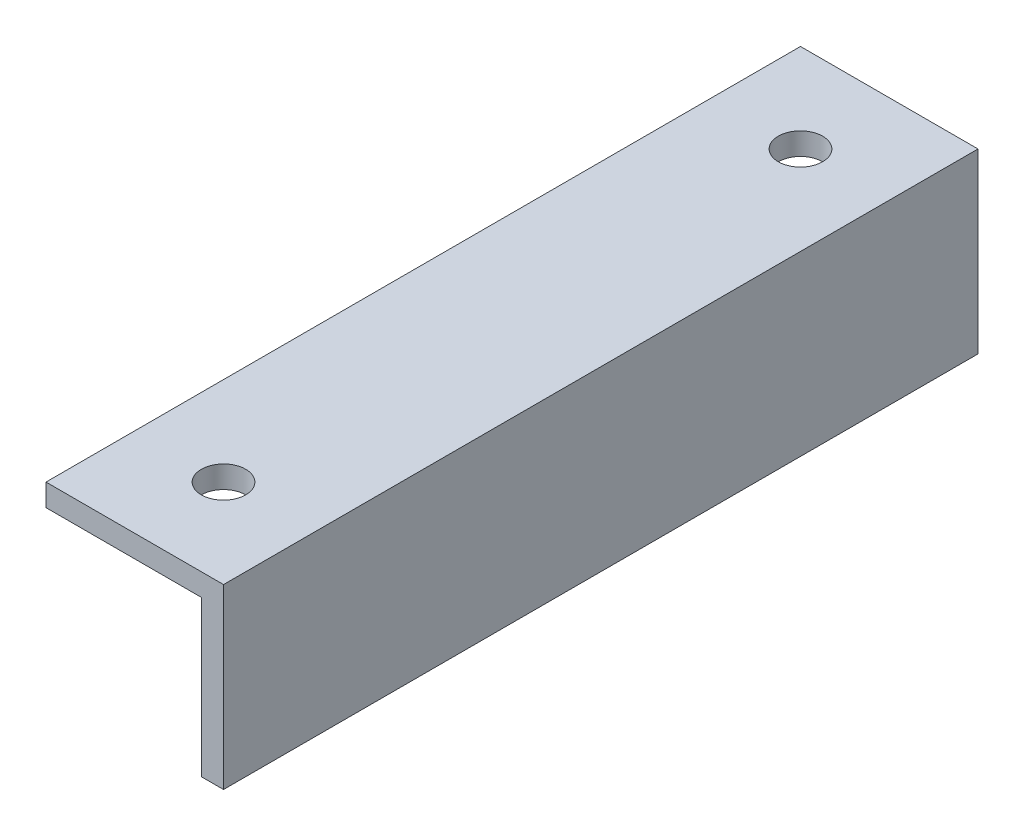
SolidWorks part; units mm, degrees
material "6061 Alloy"
ref_plane "Front Plane" through (0, 0, 0) normal (0, 0, 1) x (1, 0, 0)
ref_plane "Top Plane" through (0, 0, 0) normal (0, 1, 0) x (1, 0, 0)
ref_plane "Right Plane" through (0, 0, 0) normal (1, 0, 0) x (0, 0, -1)
sketch "Sketch1" plane through (0, 0, 0) normal (0, 0, 1) x (1, 0, 0)
  line L0 (0, 0) -> (25.4, 0)
  line L1 (25.4, 0) -> (25.4, -25.4)
  line L2 (0, 0) -> (0, -3.175)
  line L3 (25.4, -25.4) -> (22.225, -25.4)
  line L4 (22.225, -25.4) -> (22.225, -3.175)
  line L5 (22.225, -3.175) -> (0, -3.175)
extrude "Boss-Extrude1" add sketch "Sketch1" along normal blind 107.95 contours L0 L1 L3 L4 L5 L2
sketch "Sketch2" plane through (0, -3.175, 0) normal (0, -1, 0) x (1, 0, 0)
  line L0 (0, 107.95) -> (0, 0) construction
  line L1 (22.225, 0) -> (0, 0) construction
  line L2 (22.225, 107.95) -> (0, 107.95) construction
  circle A0 centre (12.7, 12.7) radius 3.175
  circle A1 centre (12.7, 95.25) radius 3.175
  dimension "D1" = 12.7
  dimension "D3" = 12.7
  dimension "D4" = 12.7
  dimension "D2" = 12.7
extrude "Cut-Extrude1" cut sketch "Sketch2" against normal up to next
